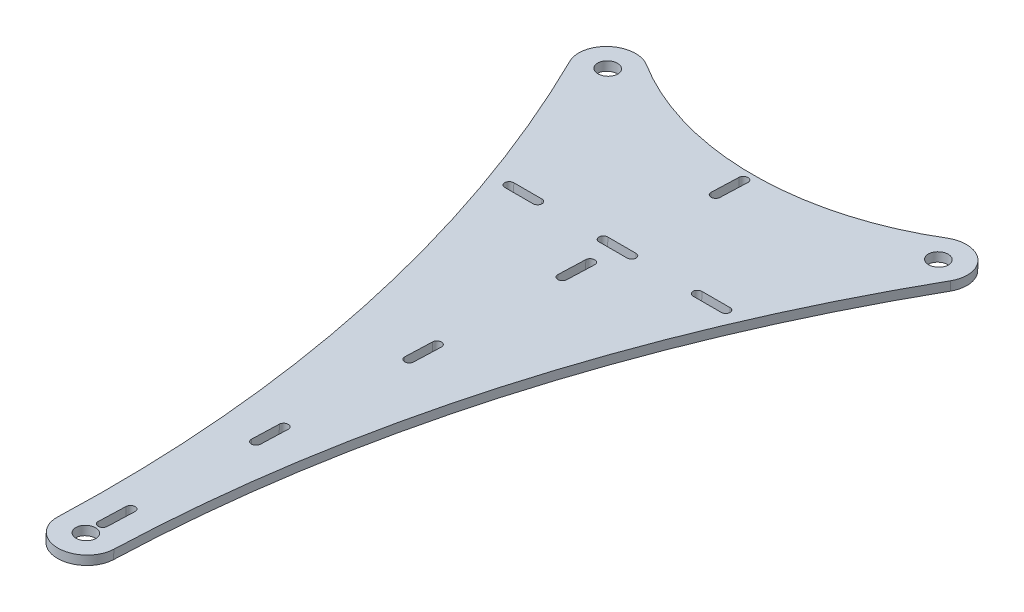
SolidWorks part; units mm, degrees
ref_plane "Front Plane" through (0, 0, 0) normal (0, 0, 1) x (1, 0, 0)
ref_plane "Top Plane" through (0, 0, 0) normal (0, 1, 0) x (1, 0, 0)
ref_plane "Right Plane" through (0, 0, 0) normal (1, 0, 0) x (0, 0, -1)
sketch "Sketch1" plane through (0, 79.1663, -2.7669) normal (0, -0.9994, 0.0349) x (0, -0.0349, -0.9994)
  line L0 (4.8479, 0) -> (-4.8479, 0) construction
  circle A0 centre (-118.8704, 0) radius 3.5
  circle A1 centre (126.4846, -59) radius 3.5
  circle A2 centre (126.4846, 59) radius 3.5
  circle A3 centre (-118.8704, 0) radius 10
  circle A4 centre (126.4846, -59) radius 10
  circle A5 centre (126.4846, 59) radius 10
  arc A6 (134.9245, 53.6364) -> (134.9245, -53.6364) centre (219.3232, 0) ccw
  arc A7 (121.9382, -67.9067) -> (-118.8704, -10) centre (-118.8704, -539.6619) ccw
  arc A8 (121.9382, 67.9067) -> (-118.8704, 10) centre (-118.8704, 539.6619) cw
  ellipse E0 centre (-118.8704, 0) end of major axis (-118.8704, 3.225) minor radius 3.223 construction
  ellipse E3 centre (126.9846, -59) end of major axis (126.9846, -56.075) minor radius 2.9032 construction
  point P16 (126.9846, -59)
  dimension "D1" = 7
  dimension "D3" = 7
  dimension "D4" = 20
  dimension "D5" = 100
  dimension "D2" = 0.5
extrude "Boss-Extrude1" add sketch "Sketch1" along normal blind 3.175 contours A5 A8 A3 A7 A4 A6 | A3 A0 | A5 A2 | A4 A1
sketch "Sketch2" plane through (0, 75.9932, -2.656) normal (0, -0.9994, 0.0349) x (1, 0, 0)
  line L0 (0, 112.8704) -> (0, 102.8704) construction
  line L1 (1.5875, 112.8704) -> (-1.5875, 112.8704) construction
  line L2 (1.5875, 102.8704) -> (-1.5875, 102.8704) construction
  line L3 (1.5875, 112.8704) -> (1.5875, 102.8704)
  line L4 (-1.5875, 112.8704) -> (-1.5875, 102.8704)
  line L5 (0, -105.9382) -> (0, -115.9382) construction
  line L6 (1.5875, -105.9382) -> (-1.5875, -105.9382) construction
  line L7 (1.5875, -115.9382) -> (-1.5875, -115.9382) construction
  line L8 (1.5875, -105.9382) -> (1.5875, -115.9382)
  line L9 (-1.5875, -105.9382) -> (-1.5875, -115.9382)
  line L10 (0, 58.1683) -> (0, 48.1683) construction
  line L11 (1.5875, 58.1683) -> (1.5875, 48.1683)
  line L12 (-1.5875, 58.1683) -> (-1.5875, 48.1683)
  line L13 (0, 3.4661) -> (0, -6.5339) construction
  line L14 (1.5875, 3.4661) -> (1.5875, -6.5339)
  line L15 (-1.5875, 3.4661) -> (-1.5875, -6.5339)
  line L16 (0, -51.236) -> (0, -61.236) construction
  line L17 (1.5875, -51.236) -> (1.5875, -61.236)
  line L18 (-1.5875, -51.236) -> (-1.5875, -61.236)
  line L19 (1.5875, -6.5339) -> (-1.5875, -6.5339) construction
  line L20 (38.5715, -70.9382) -> (28.5715, -70.9382) construction
  line L21 (38.5715, -72.5257) -> (38.5715, -69.3507) construction
  line L22 (28.5715, -72.5257) -> (28.5715, -69.3507) construction
  line L23 (38.5715, -72.5257) -> (28.5715, -72.5257)
  line L24 (38.5715, -69.3507) -> (28.5715, -69.3507)
  line L25 (5, -70.9382) -> (-5, -70.9382) construction
  line L26 (5, -72.5257) -> (5, -69.3507) construction
  line L27 (-5, -72.5257) -> (-5, -69.3507) construction
  line L28 (5, -72.5257) -> (-5, -72.5257)
  line L29 (5, -69.3507) -> (-5, -69.3507)
  line L30 (-28.5715, -70.9382) -> (-38.5715, -70.9382) construction
  line L31 (-28.5715, -72.5257) -> (-28.5715, -69.3507) construction
  line L32 (-38.5715, -72.5257) -> (-38.5715, -69.3507) construction
  line L33 (-28.5715, -72.5257) -> (-38.5715, -72.5257)
  line L34 (-28.5715, -69.3507) -> (-38.5715, -69.3507)
  arc A0 (1.5875, 112.8704) -> (-1.5875, 112.8704) centre (0, 112.8704) ccw
  arc A1 (-1.5875, 102.8704) -> (1.5875, 102.8704) centre (0, 102.8704) ccw
  arc A2 (1.5875, -105.9382) -> (-1.5875, -105.9382) centre (0, -105.9382) ccw
  arc A3 (-1.5875, -115.9382) -> (1.5875, -115.9382) centre (0, -115.9382) ccw
  arc A4 (1.5875, 58.1683) -> (-1.5875, 58.1683) centre (0, 58.1683) ccw
  arc A5 (-1.5875, 48.1683) -> (1.5875, 48.1683) centre (0, 48.1683) ccw
  arc A6 (1.5875, 3.4661) -> (-1.5875, 3.4661) centre (0, 3.4661) ccw
  arc A7 (-1.5875, -6.5339) -> (1.5875, -6.5339) centre (0, -6.5339) ccw
  arc A8 (1.5875, -51.236) -> (-1.5875, -51.236) centre (0, -51.236) ccw
  arc A9 (-1.5875, -61.236) -> (1.5875, -61.236) centre (0, -61.236) ccw
  arc A10 (38.5715, -72.5257) -> (38.5715, -69.3507) centre (38.5715, -70.9382) ccw
  arc A11 (28.5715, -69.3507) -> (28.5715, -72.5257) centre (28.5715, -70.9382) ccw
  arc A12 (5, -72.5257) -> (5, -69.3507) centre (5, -70.9382) ccw
  arc A13 (-5, -69.3507) -> (-5, -72.5257) centre (-5, -70.9382) ccw
  arc A14 (-28.5715, -72.5257) -> (-28.5715, -69.3507) centre (-28.5715, -70.9382) ccw
  arc A15 (-38.5715, -69.3507) -> (-38.5715, -72.5257) centre (-38.5715, -70.9382) ccw
  point P6 (0, 107.8704)
  point P11 (0, -110.9382)
  point P22 (33.5715, -70.9382)
  point P28 (0, 53.1683)
  point P35 (0, -1.5339)
  point P42 (0, -56.236)
  point P59 (0, -70.9382)
  point P70 (-33.5715, -70.9382)
  dimension "D1" = 4
extrude "Cut-Extrude1" cut sketch "Sketch2" against normal blind 3.175
